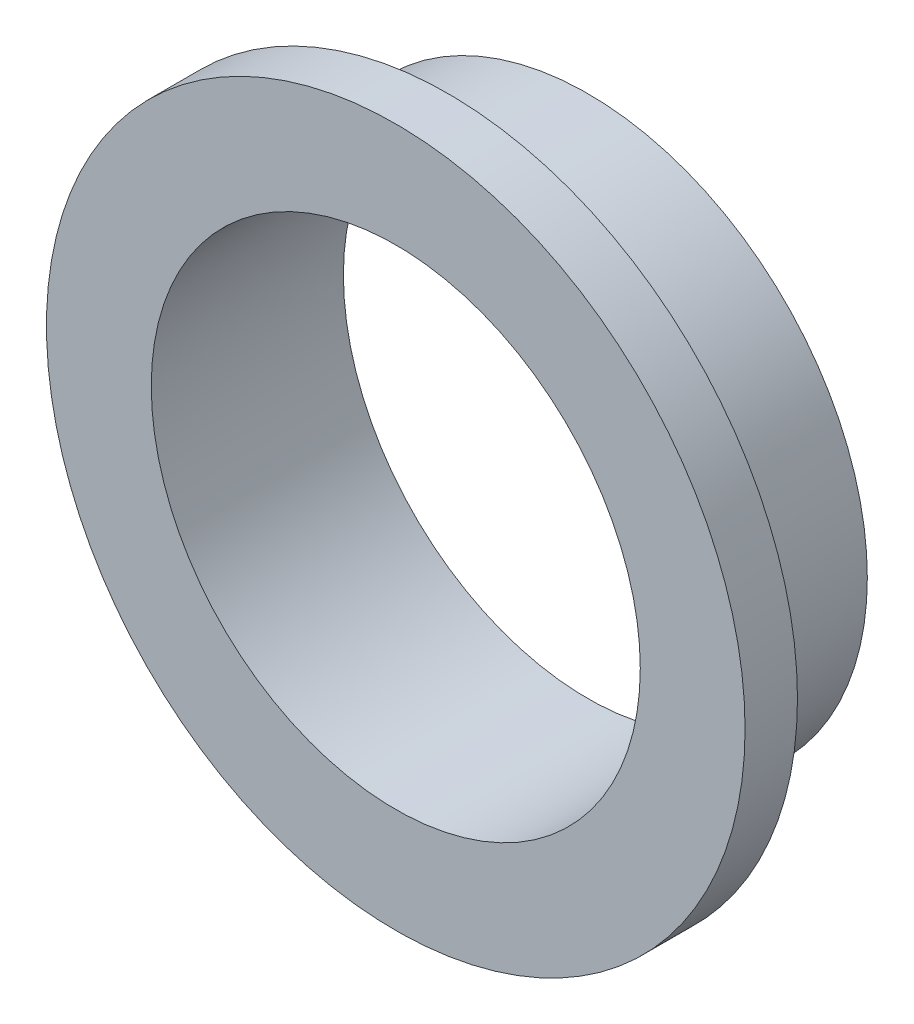
SolidWorks part; units mm, degrees
ref_plane "前视基准面" through (0, 0, 0) normal (0, 0, 1) x (1, 0, 0)
ref_plane "上视基准面" through (0, 0, 0) normal (0, 1, 0) x (1, 0, 0)
ref_plane "右视基准面" through (0, 0, 0) normal (1, 0, 0) x (0, 0, -1)
sketch "草图1" plane through (0, 0, 0) normal (0, 0, 1) x (1, 0, 0)
  circle A0 centre (0, 0) radius 16
  circle A1 centre (0, 0) radius 14
  dimension "D1" = 28
  dimension "D2" = 32
extrude "凸台-拉伸1" add sketch "草图1" along normal blind 8
sketch "草图2" plane through (0, 0, 8) normal (0, 0, 1) x (1, 0, 0)
  circle A0 centre (0, 0) radius 20
  circle A1 centre (0, 0) radius 14
  dimension "D1" = 40
extrude "凸台-拉伸2" add sketch "草图2" along normal blind 3
